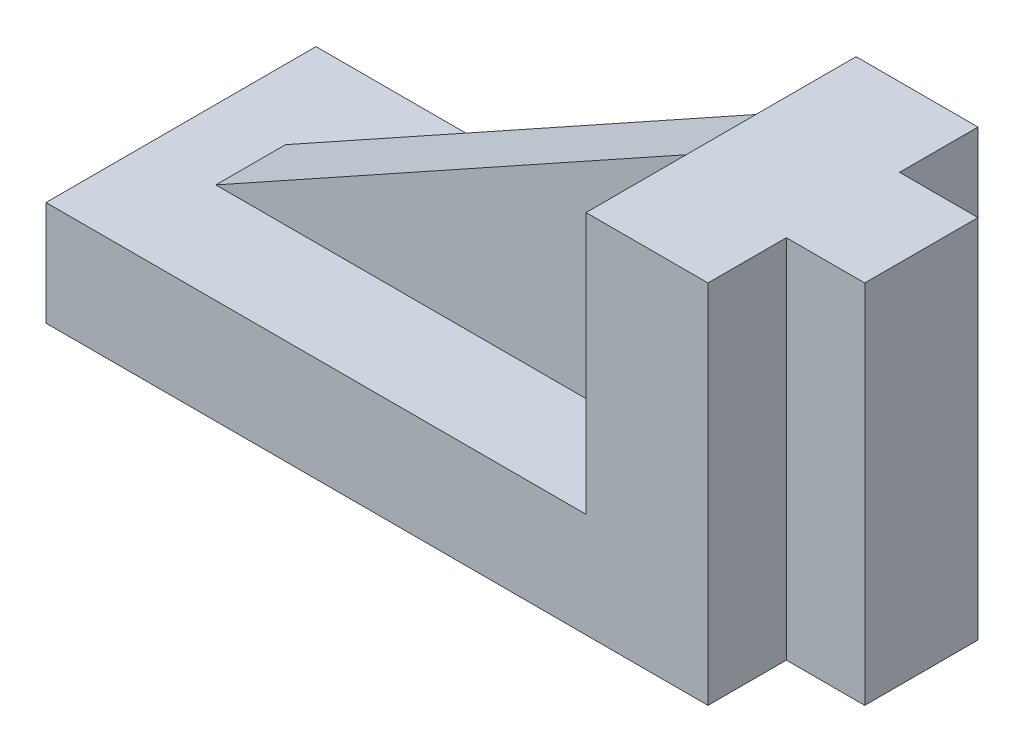
SolidWorks part; units mm, degrees
ref_plane "Front Plane" through (0, 0, 0) normal (0, 0, 1) x (1, 0, 0)
ref_plane "Top Plane" through (0, 0, 0) normal (0, 1, 0) x (1, 0, 0)
ref_plane "Right Plane" through (0, 0, 0) normal (1, 0, 0) x (0, 0, -1)
sketch "Sketch1" plane through (0, 0, 0) normal (0, 0, 1) x (1, 0, 0)
  line L0 (0, 0) -> (0, 12)
  line L1 (0, 12) -> (62, 12)
  line L2 (62, 12) -> (62, 42)
  line L3 (62, 42) -> (76, 42)
  line L4 (76, 42) -> (76, 0)
  line L5 (76, 0) -> (0, 0)
  dimension "D1" = 12
  dimension "D2" = 76
  dimension "D3" = 42
  dimension "D4" = 14
extrude "Boss-Extrude1" add sketch "Sketch1" along normal mid plane 31
sketch "Sketch2" plane through (0, 0, 0) normal (0, 0, 1) x (1, 0, 0)
  line L0 (8, 12) -> (62, 42)
  line L1 (62, 12) -> (0, 12) construction
  line L2 (62, 42) -> (62, 12)
  line L3 (62, 12) -> (8, 12)
  line L4 (0, 12) -> (0, 0) construction
  dimension "D1" = 8
extrude "Boss-Extrude2" add sketch "Sketch2" along normal mid plane 8
sketch "Sketch3" plane through (0, 42, 0) normal (0, 1, 0) x (1, 0, 0)
  line L5 (76, -15.5) -> (76, 15.5) construction
  line L6 (76, 6.5) -> (85, 6.5)
  line L7 (76, 6.5) -> (76, -6.5)
  line L8 (76, -6.5) -> (85, -6.5)
  line L9 (85, 6.5) -> (85, -6.5)
  line L10 (76, -15.5) -> (62, -15.5) construction
  dimension "D1" = 13
  dimension "D2" = 9
  dimension "D3" = 9
extrude "Boss-Extrude3" add sketch "Sketch3" against normal through all
equation "\"`13\"=8.85503"
